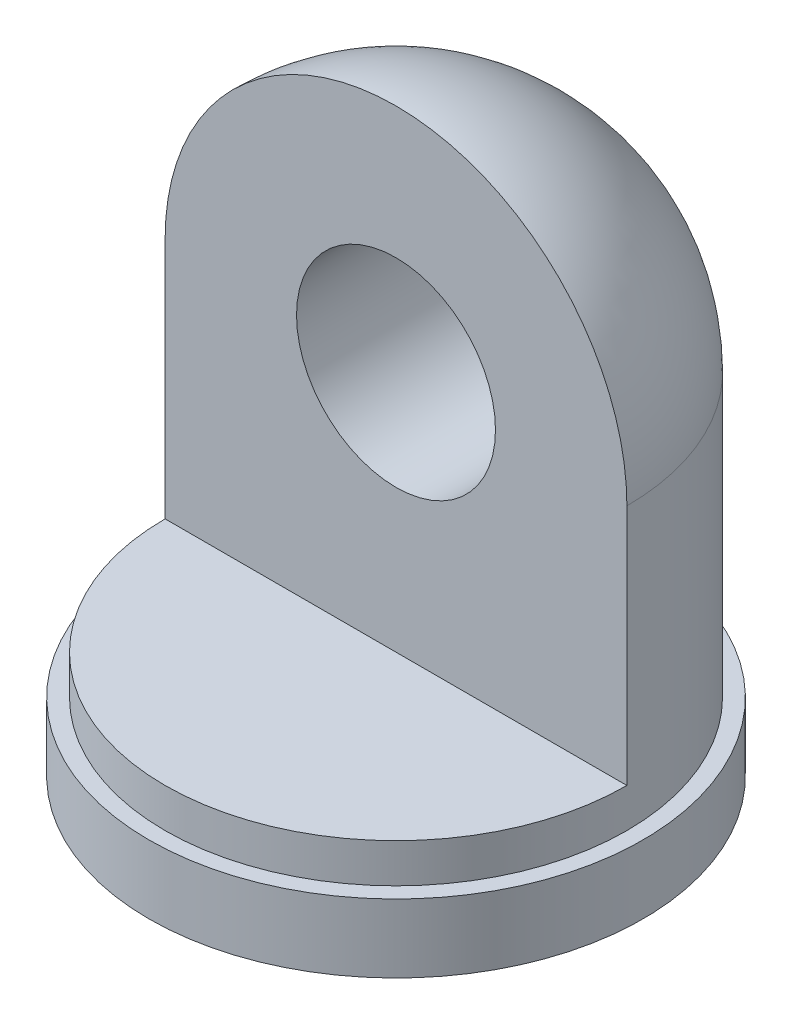
SolidWorks part; units mm, degrees
ref_plane "Front Plane" through (0, 0, 0) normal (0, 0, 1) x (1, 0, 0)
ref_plane "Top Plane" through (0, 0, 0) normal (0, 1, 0) x (1, 0, 0)
ref_plane "Right Plane" through (0, 0, 0) normal (1, 0, 0) x (0, 0, -1)
sketch "Sketch1" plane through (0, 0, 0) normal (0, 0, 1) x (1, 0, 0)
  line L0 (-6, 0) -> (-6, 6.2933)
  line L1 (0, 12.2933) -> (0, 0)
  line L2 (-6, 0) -> (0, 0)
  arc A0 (-6, 6.2933) -> (0, 12.2933) centre (0, 6.2933) cw
  dimension "D1" = 6
  dimension "D2" = 12.2933
revolve "Revolve1" add sketch "Sketch1" angle 180 about L1
sketch "Sketch2" plane through (0, 0, 0) normal (0, -1, 0) x (1, 0, 0)
  circle A0 centre (0, 0) radius 6
extrude "Extrude1" add sketch "Sketch2" along normal blind 1.016
sketch "Sketch3" plane through (0, -1.016, 0) normal (0, -1, 0) x (1, 0, 0)
  circle A0 centre (0, 0) radius 6.419
extrude "Extrude2" add sketch "Sketch3" along normal blind 1.778
sketch "Sketch4" plane through (0, 0, 0) normal (0, 0, 1) x (1, 0, 0)
  circle A0 centre (0, 6.2933) radius 2.5849
  arc A1 (6, 6.2933) -> (-6, 6.2933) centre (0, 6.2933) ccw construction
extrude "Extrude3" cut sketch "Sketch4" against normal through all
